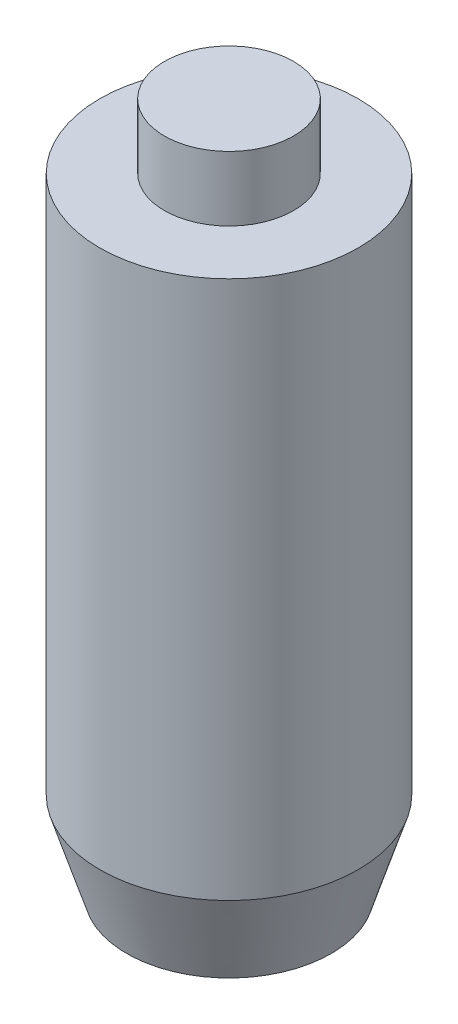
SolidWorks part; units mm, degrees
ref_plane "Plano frontal" through (0, 0, 0) normal (0, 0, 1) x (1, 0, 0)
ref_plane "Plano superior" through (0, 0, 0) normal (0, 1, 0) x (1, 0, 0)
ref_plane "Plano direito" through (0, 0, 0) normal (1, 0, 0) x (0, 0, -1)
ref_point "Ponto1"
ref_axis "Eixo1" through (29.75, 33.4895, 0) along (0, 1, 0)
sketch "Esboço1" plane through (0, 0, 0) normal (0, 0, 1) x (1, 0, 0)
  line L0 (29.75, 112.5) -> (29.75, 105.5)
  line L1 (32, 90) -> (27.5, 90) construction
  line L2 (29.75, 112.5) -> (32.75, 112.5)
  line L3 (32.75, 112.5) -> (32.75, 109.5)
  line L4 (32.75, 109.5) -> (35.75, 109.5)
  line L5 (35.75, 109.5) -> (35.75, 84.5)
  line L6 (35.75, 84.5) -> (34.5, 80.5)
  line L7 (34.5, 80.5) -> (32, 80.5)
  line L8 (32, 0) -> (32, 90) construction
  line L9 (32, 80.5) -> (32, 105.5)
  line L10 (29.75, 105.5) -> (32, 105.5)
  dimension "D1" = 6
  dimension "D2" = 2.5
  dimension "D3" = 3
  dimension "D4" = 2.25
  dimension "D5" = 7
  dimension "D6" = 3
  dimension "D7" = 25
  dimension "D8" = 25
  dimension "D9" = 15.5
revolve "Revolução1" add sketch "Esboço1" angle 360 about axis through (29.75, 33.4895, 0) along (0, 1, 0)
ref_plane "Plano1" through (0, 0, -6) normal (0, 0, -1) x (-1, 0, 0)
hole_wizard "Rebaixo para SBHCS M36" positions "Esboço11" profile "Esboço12" counterbore size "M3" standard "Métrico Ansi"
sketch "Esboço11" plane through (0, 0, -6) normal (0, 0, -1) x (-1, 0, 0)
  line L0 (-23.75, 109.5) -> (-35.75, 109.5) construction
  line L1 (-35.75, 109.5) -> (-35.75, 84.5) construction
  point P0 (-29.75, 99.5)
  dimension "D1" = 10
  dimension "D2" = 6
sketch "Esboço12" plane through (29.75, 99.5, -6) normal (1, 0, 0) x (0, 1, 0)
  line L0 (0, 0) -> (0, 6.0215)
  line L1 (0, 6.0215) -> (1.7, 5)
  line L2 (1.7, 5) -> (1.7, 1.65)
  line L3 (1.7, 1.65) -> (3.35, 1.65)
  line L4 (3.35, 1.65) -> (3.35, 0)
  line L5 (3.35, 0) -> (0, 0)
  line L10 (0, 6.0215) -> (-1.7, 5) construction
  line L11 (0, -6.35) -> (0, 107.95) construction
  dimension "Hole Dia." = 3.4
  dimension "Hole Depth" = 5
  dimension "C'Bore Dia." = 6.7
  dimension "C'Bore Depth" = 1.65
  dimension "Drill Angle" = 118
